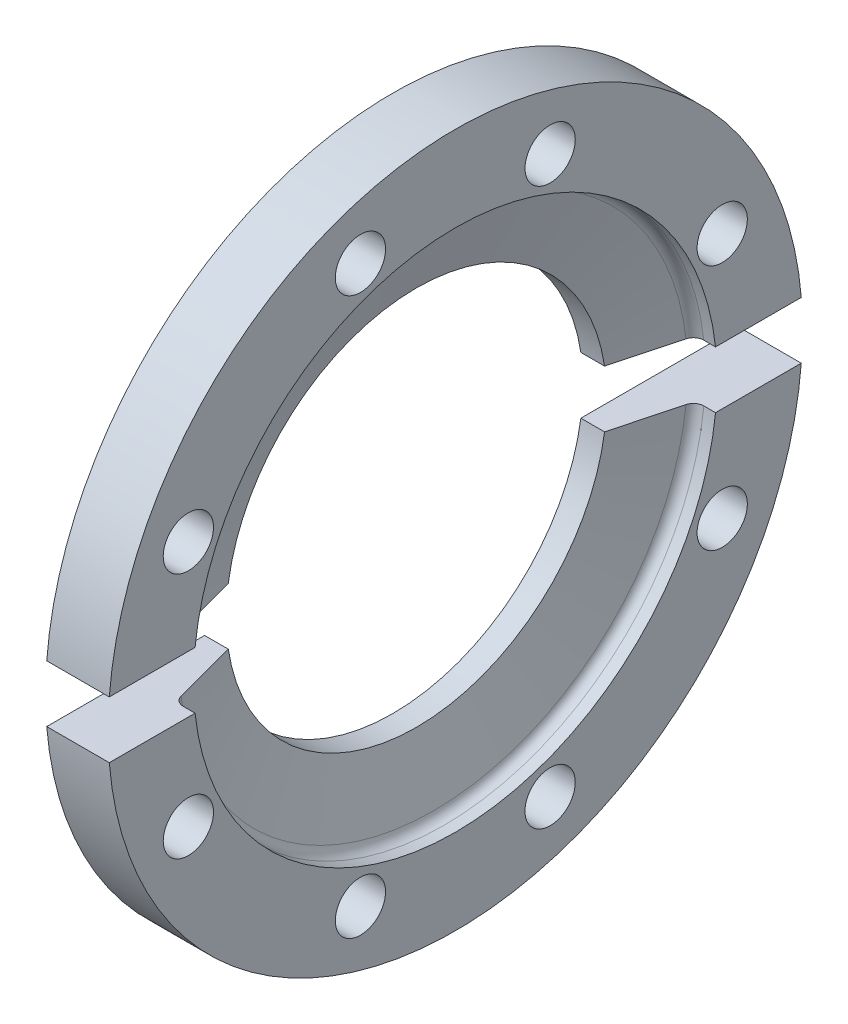
SolidWorks part; units mm, degrees
ref_plane "Front Plane" through (0, 0, 0) normal (0, 0, 1) x (1, 0, 0)
ref_plane "Top Plane" through (0, 0, 0) normal (0, 1, 0) x (1, 0, 0)
ref_plane "Right Plane" through (0, 0, 0) normal (1, 0, 0) x (0, 0, -1)
sketch "Sketch3" plane through (0, 27.8258, 0) normal (0, 1, 0) x (0, 0, 1)
  line L3 (41.6884, -43.7117) -> (50.6884, -43.7117) construction
  line L4 (34.1493, -48.8082) -> (34.1493, -51.3082)
  line L5 (41.6884, -45.9441) -> (41.6884, -43.7117)
  line L6 (34.1493, -48.8082) -> (40.8731, -47.0066)
  line L7 (41.6884, -45.9441) -> (41.6884, -43.7117)
  line L8 (34.1493, -48.8082) -> (40.8731, -47.0066)
  line L9 (50.6884, -43.7117) -> (50.6884, -51.3082)
  line L10 (50.6884, -51.3082) -> (34.1493, -51.3082)
  line L11 (-5.9466, -48.7117) -> (34.1234, -48.7117) construction
  line L12 (-5.9466, -48.7117) -> (34.1234, -48.7117)
  line L13 (14.0884, -48.7117) -> (14.0884, -55.74)
  line L14 (41.6884, -44.7117) -> (50.6884, -44.7117)
  arc A3 (40.8731, -47.0066) -> (41.6884, -45.9441) centre (40.5884, -45.9441) ccw
  arc A4 (40.8731, -47.0066) -> (41.6884, -45.9441) centre (40.5884, -45.9441) ccw
  dimension "D2" = 9
  dimension "D3" = 2.5
  dimension "D4" = 1
  dimension "D1" = 0.1
revolve "Revolve1" add sketch "Sketch3" angle 360 about L13
sketch "Sketch4" plane through (-51.3082, 0, 0) normal (-1, 0, 0) x (0, 0, 1)
  line L0 (34.1493, 27.8258) -> (50.6884, 27.8258) construction
  line L1 (50.6884, 27.8258) -> (-22.5116, 27.8258) construction
  line L2 (50.6884, 24.8258) -> (-22.5116, 24.8258)
  line L3 (50.6884, 30.8258) -> (-22.5116, 30.8258)
  line L4 (14.0884, 64.4258) -> (14.0884, -8.7742) construction
  line L5 (4.0884, 58.8258) -> (24.0884, 58.8258) construction
  line L6 (4.0884, 58.8258) -> (4.0884, 57.1686) construction
  line L7 (24.0884, 58.8258) -> (24.0884, 57.1686) construction
  line L8 (44.9429, 30.8258) -> (44.9429, 40.8258) construction
  line L9 (44.9429, 40.8258) -> (42.2309, 40.8258) construction
  circle A0 centre (14.0884, 27.8258) radius 20.0609 construction
  circle A1 centre (14.0884, 27.8258) radius 36.6
  circle A2 centre (14.0884, 27.8258) radius 36.6 construction
  circle A3 centre (14.0884, 27.8258) radius 20.0609 construction
  circle A4 centre (14.0884, 27.8258) radius 31 construction
  circle A5 centre (42.2309, 40.8258) radius 2.65
  circle A6 centre (24.0884, 57.1686) radius 2.65
  circle A7 centre (-14.0541, 40.8258) radius 2.65
  circle A8 centre (4.0884, 57.1686) radius 2.65
  circle A9 centre (42.2309, 14.8258) radius 2.65
  circle A10 centre (24.0884, -1.517) radius 2.65
  circle A11 centre (4.0884, -1.517) radius 2.65
  circle A12 centre (-14.0541, 14.8258) radius 2.65
  point P18 (14.0884, 27.8258)
  point P21 (14.0884, 58.8258)
  circle M14 centre (14.0884, 27.8258) radius 20.0609
  circle M15 centre (14.0884, 27.8258) radius 36.6
  dimension "D2" = 3
  dimension "D6" = 5.3
  dimension "D7" = 62
  dimension "D4" = 20
  dimension "D5" = 10
  dimension "D1" = 0
  dimension "D3" = 3
extrude "Cut-Extrude1" cut sketch "Sketch4" against normal blind 10 contours L3 L2 M14 M15 | L3 L2 M14 | L3 L2 M15 M14 | A6 | A8 | A7 | A12 | A11 | A10 | A9 | A5
